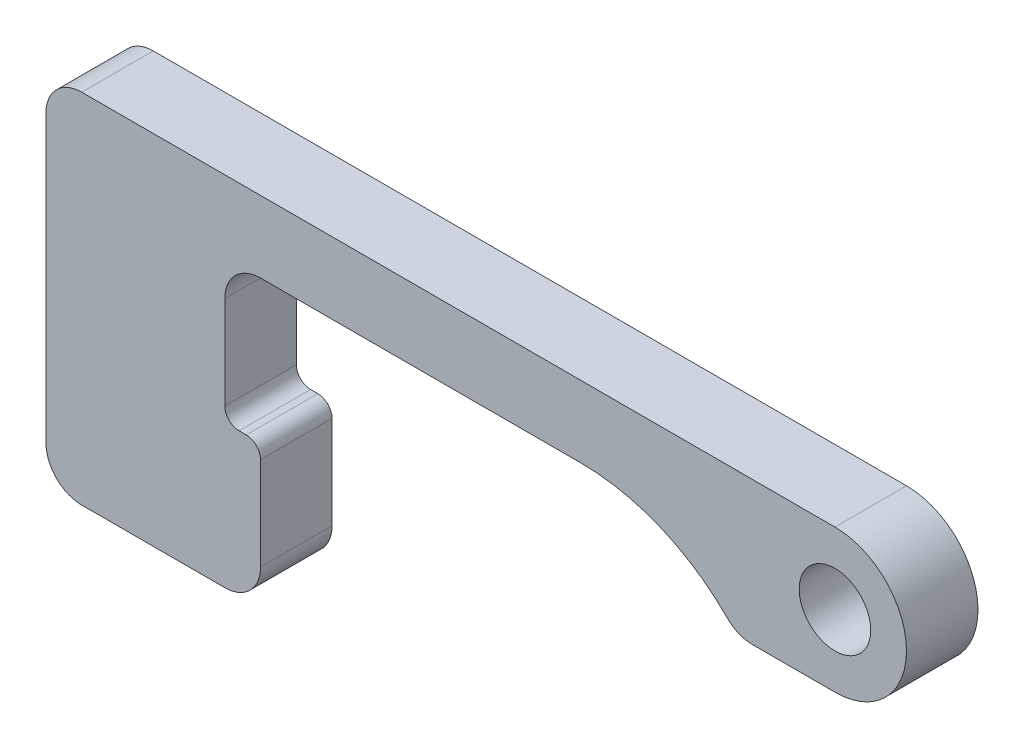
SolidWorks part; units mm, degrees
ref_plane "Front Plane" through (0, 0, 0) normal (0, 0, 1) x (1, 0, 0)
ref_plane "Top Plane" through (0, 0, 0) normal (0, 1, 0) x (1, 0, 0)
ref_plane "Right Plane" through (0, 0, 0) normal (1, 0, 0) x (0, 0, -1)
sketch "Sketch1" plane through (0, 0, 0) normal (0, 0, 1) x (1, 0, 0)
  line L0 (-80.3169, -40) -> (-110.3169, -40)
  line L1 (-110.3169, -40) -> (-110.3169, 10)
  line L2 (-110.3169, 10) -> (0, 10)
  line L4 (0, -10) -> (-13.704, -10)
  line L6 (-85.3169, 0) -> (-85.3169, -20)
  line L7 (-85.3169, -20) -> (-80.3169, -20)
  line L8 (-80.3169, -20) -> (-80.3169, -40)
  line L10 (-85.3169, 0) -> (-35.5537, 0)
  arc A1 (-13.704, -10) -> (-35.5537, 0) centre (-35.5537, -28.8705) ccw
  circle A3 centre (0, 0) radius 5
  arc A4 (0, -10) -> (0, 10) centre (0, 0) ccw
  point P2 (0, 0)
  point P3 (-85.3169, 0)
  point P7 (-84.1066, 0)
  point P10 (0, 0)
  point P11 (0, 0)
  dimension "D5" = 10
  dimension "D6" = 20
  dimension "D1" = 25
  dimension "D2" = 5
  dimension "D3" = 20
  dimension "D4" = 20
  dimension "D7" = 49.7632
  dimension "D8" = 10
  dimension "D9" = 110.3169
  dimension "D10" = 21.8497
extrude "Boss-Extrude1" add sketch "Sketch1" along normal blind 10
fillet "Fillet1" radius 5 5 edges at (-13.704, -10, 5) (-110.3169, 10, 5) (-80.3169, -40, 5) (-110.3169, -40, 5) (-85.3169, 0, 5)
fillet "Fillet2" radius 2 2 edges at (-85.3169, -20, 5) (-80.3169, -20, 5)
